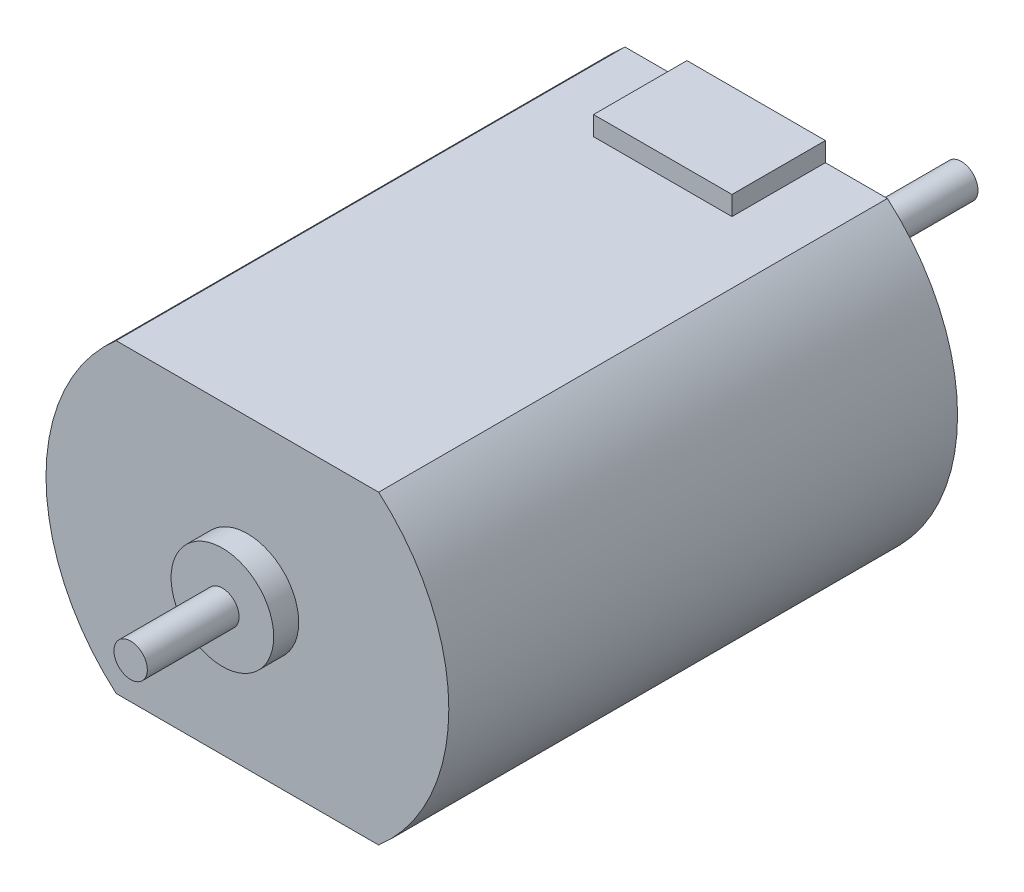
SolidWorks part; units mm, degrees
ref_plane "Front Plane" through (0, 0, 0) normal (0, 0, 1) x (1, 0, 0)
ref_plane "Top Plane" through (0, 0, 0) normal (0, 1, 0) x (1, 0, 0)
ref_plane "Right Plane" through (0, 0, 0) normal (1, 0, 0) x (0, 0, -1)
sketch "Sketch1" plane through (0, 0, 0) normal (0, 0, 1) x (1, 0, 0)
  line L1 (-7.8677, -9.16) -> (7.8677, -9.16)
  line L3 (-7.8677, 9.16) -> (7.8677, 9.16)
  line L5 (-7.8677, -9.16) -> (7.8677, 9.16) construction
  line L6 (-7.8677, 9.16) -> (7.8677, -9.16) construction
  arc A0 (-7.8677, 9.16) -> (-7.8677, -9.16) centre (0, 0) ccw
  arc A1 (7.8677, -9.16) -> (7.8677, 9.16) centre (0, 0) ccw
  point P0 (0, 0)
  point P8 (7.7171, 9.16)
  point P9 (7.9809, -9.0615)
  dimension "D2" = 24.15
  dimension "D1" = 18.32
extrude "Main Body" add sketch "Sketch1" along normal blind 30.5
sketch "Sketch2" plane through (0, 0, 0) normal (0, 0, -1) x (-1, 0, 0)
  circle A0 centre (0, 0) radius 4.23
  dimension "D1" = 8.46
extrude "Long Shaft Collar" add sketch "Sketch2" along normal blind 2
sketch "Sketch3" plane through (0, 0, -2) normal (0, 0, -1) x (-1, 0, 0)
  circle A0 centre (0, 0) radius 1
  dimension "D1" = 2
extrude "Long Shaft" add sketch "Sketch3" along normal blind 10.3
sketch "Sketch5" plane through (0, 9.16, 0) normal (0, 1, 0) x (1, 0, 0)
  line L0 (7.8677, 0) -> (-7.8677, 0) construction
  line L2 (-4.15, 0) -> (4.15, 0)
  line L3 (-4.15, 0) -> (-4.15, -5.6)
  line L4 (-4.15, -5.6) -> (4.15, -5.6)
  line L5 (4.15, 0) -> (4.15, -5.6)
  point P6 (0, 0)
  point P7 (4.0826, 0)
  dimension "D1" = 8.3
  dimension "D2" = 5.6
extrude "Lead Bump" add sketch "Sketch5" along normal blind 1.15
sketch "Sketch6" plane through (0, 0, 30.5) normal (0, 0, 1) x (1, 0, 0)
  circle A0 centre (0, 0) radius 3.075
  dimension "D1" = 6.15
extrude "Short Shaft Collar" add sketch "Sketch6" along normal blind 1.5
sketch "Sketch7" plane through (0, 0, 32) normal (0, 0, 1) x (1, 0, 0)
  circle A0 centre (0, 0) radius 1
  dimension "D1" = 2
extrude "Short shaft" add sketch "Sketch7" along normal blind 5.5
